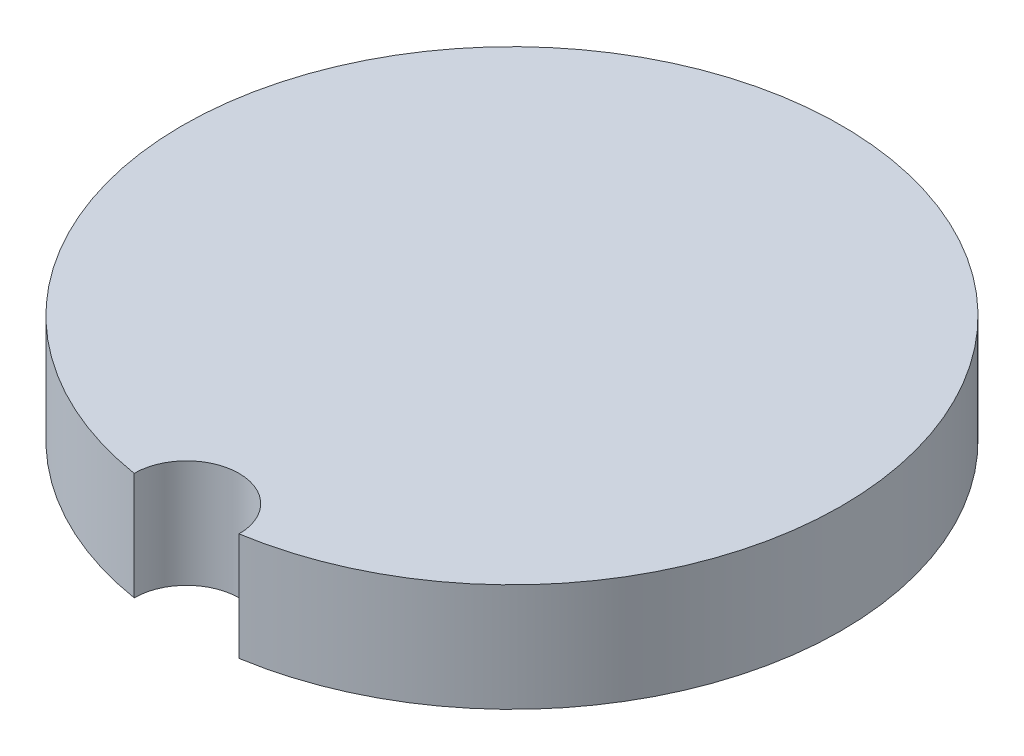
SolidWorks part; units mm, degrees
ref_plane "Front Plane" through (0, 0, 0) normal (0, 0, 1) x (1, 0, 0)
ref_plane "Top Plane" through (0, 0, 0) normal (0, 1, 0) x (1, 0, 0)
ref_plane "Right Plane" through (0, 0, 0) normal (1, 0, 0) x (0, 0, -1)
sketch "Sketch1" plane through (0, 0, 0) normal (0, 1, 0) x (1, 0, 0)
  circle A0 centre (0, 0) radius 22
  dimension "D1" = 44
extrude "Boss-Extrude1" add sketch "Sketch1" along normal blind 7.2
sketch "Sketch2" plane through (0, 0, 0) normal (0, -1, 0) x (1, 0, 0)
  line L1 (3.5, -21.7198) -> (-3.5, -21.7198)
  line L2 (3.5, -21.7198) -> (3.5, 21.7198)
  line L3 (3.5, 21.7198) -> (-3.5, 21.7198)
  line L4 (-3.5, -21.7198) -> (-3.5, 21.7198)
  line L5 (3.5, -21.7198) -> (-3.5, 21.7198) construction
  line L6 (3.5, 21.7198) -> (-3.5, -21.7198) construction
  circle A0 centre (0, 0) radius 22 construction
  circle A1 centre (0, 21.7198) radius 3.5
  point P0 (0, 0)
  circle M2 centre (0, 0) radius 22
  dimension "D1" = 7
extrude "Cut-Extrude1" cut sketch "Sketch2" against normal through all contours L3 A1 | A1 M2 | L3 M2
